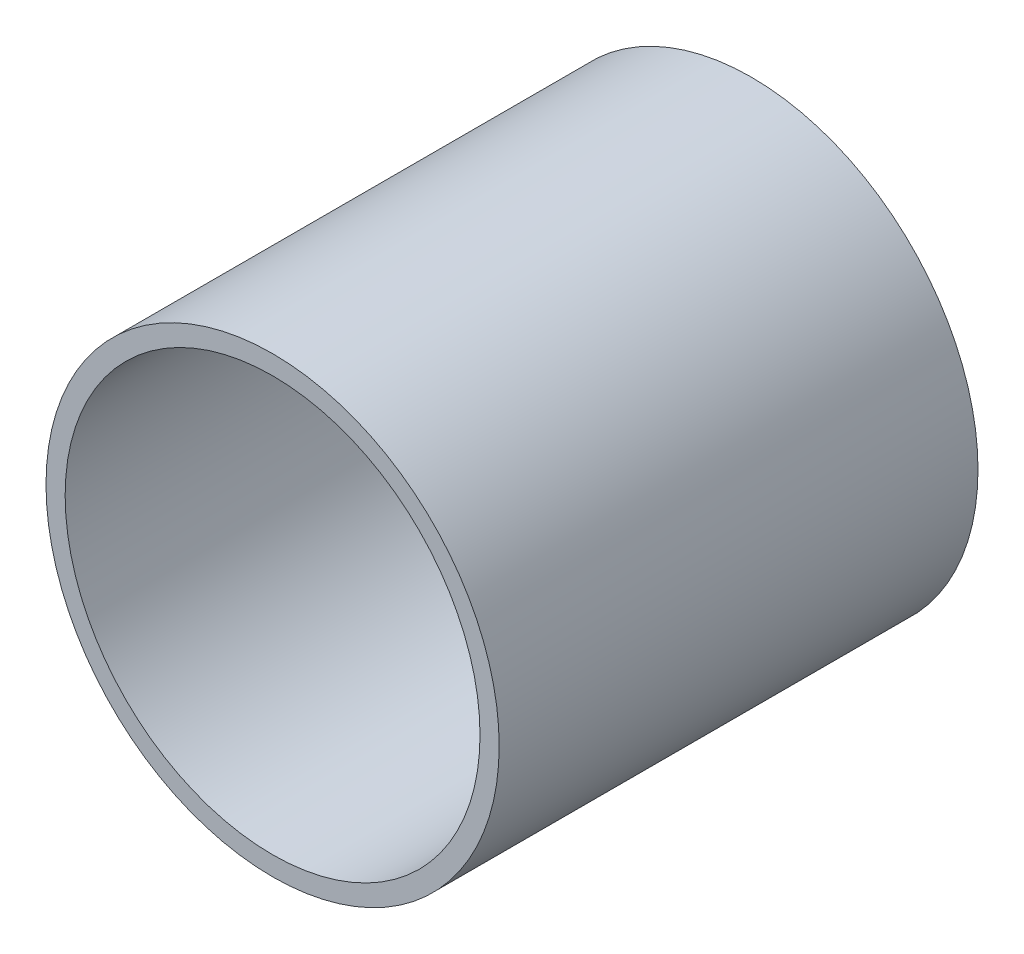
SolidWorks part; units mm, degrees
ref_plane "Plane1" through (0, 0, 0) normal (0, 0, 1) x (1, 0, 0)
ref_plane "Plane2" through (0, 0, 0) normal (0, 1, 0) x (1, 0, 0)
ref_plane "Plane3" through (0, 0, 0) normal (1, 0, 0) x (0, 0, -1)
sketch "Sketch1" plane through (0, 0, 0) normal (0, 0, 1) x (1, 0, 0)
  circle A0 centre (0, 0) radius 77.0255
  circle A1 centre (0, 0) radius 84.1375
extrude "BasePipe" add sketch "Sketch1" along normal mid plane 177.8
